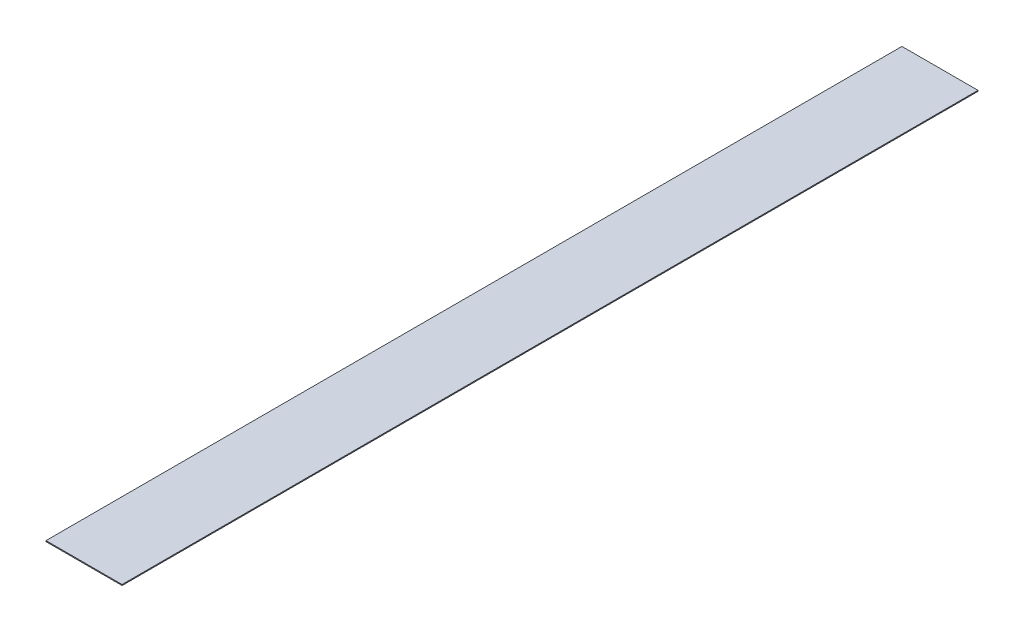
SolidWorks part; units mm, degrees
ref_plane "Front Plane" through (0, 0, 0) normal (0, 0, 1) x (1, 0, 0)
ref_plane "Top Plane" through (0, 0, 0) normal (0, 1, 0) x (1, 0, 0)
ref_plane "Right Plane" through (0, 0, 0) normal (1, 0, 0) x (0, 0, -1)
sketch "Sketch2" plane through (0, 0, 0) normal (0, 1, 0) x (1, 0, 0)
  line L0 (2, -22.5) -> (2, 22.5)
  line L1 (-2, -22.5) -> (-2, 22.5)
  line L2 (2, -22.5) -> (-2, -22.5)
  line L3 (2, 22.5) -> (-2, 22.5)
  line L4 (2, 22.5) -> (-2, -22.5) construction
  line L5 (-2, 22.5) -> (2, -22.5) construction
  point P2 (0, -22.5)
  point P5 (0, 22.5)
  point P6 (0, 0)
  dimension "D1" = 45
  dimension "D2" = 4
extrude "Boss-Extrude1" add sketch "Sketch2" along normal mid plane 0.05
